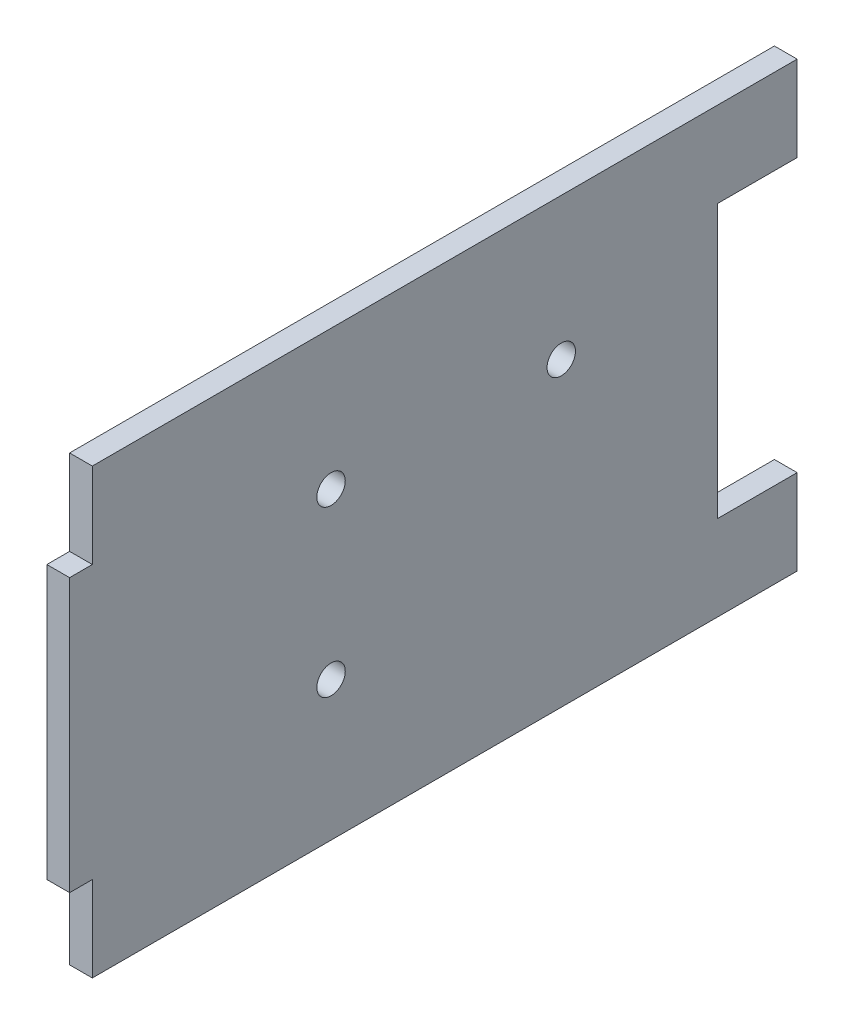
SolidWorks part; units mm, degrees
ref_plane "Front Plane" through (0, 0, 0) normal (0, 0, 1) x (1, 0, 0)
ref_plane "Top Plane" through (0, 0, 0) normal (0, 1, 0) x (1, 0, 0)
ref_plane "Right Plane" through (0, 0, 0) normal (1, 0, 0) x (0, 0, -1)
sketch "Sketch1" plane through (0, 0, 0) normal (1, 0, 0) x (0, 0, -1)
  line L0 (0, 63) -> (0, 78)
  line L1 (0, 0) -> (124, 0)
  line L2 (0, 0) -> (0, 15)
  line L3 (0, 78) -> (124, 78)
  line L4 (124, 0) -> (124, 15)
  line L5 (0, 63) -> (-4, 63)
  line L6 (124, 63) -> (124, 78)
  line L7 (0, 15) -> (-4, 15)
  line L8 (-4, 63) -> (-4, 15)
  line L9 (124, 63) -> (110, 63)
  line L11 (124, 15) -> (110, 15)
  line L12 (110, 63) -> (110, 15)
  dimension "D1" = 124
  dimension "D2" = 78
  dimension "D3" = 4
  dimension "D4" = 15
  dimension "D5" = 15
  dimension "D6" = 14
extrude "Boss-Extrude1" add sketch "Sketch1" along normal blind 4
sketch "Sketch2" plane through (4, 0, 0) normal (1, 0, 0) x (0, 0, -1)
  line L0 (0, 0) -> (124, 0) construction
  line L1 (124, 78) -> (0, 78) construction
  line L2 (0, 15) -> (0, 0) construction
  line L3 (0, 78) -> (0, 63) construction
  line L4 (124, 63) -> (124, 78) construction
  circle A0 centre (42, 24.5) radius 2.5
  circle A1 centre (42, 53.5) radius 2.5
  circle A2 centre (82.5, 53) radius 2.5
  dimension "D7" = 5
  dimension "D8" = 5
  dimension "D9" = 5
  dimension "D1" = 24.5
  dimension "D2" = 24.5
  dimension "D3" = 25
  dimension "D4" = 42
  dimension "D5" = 42
  dimension "D6" = 41.5
extrude "Cut-Extrude1" cut sketch "Sketch2" against normal through all
